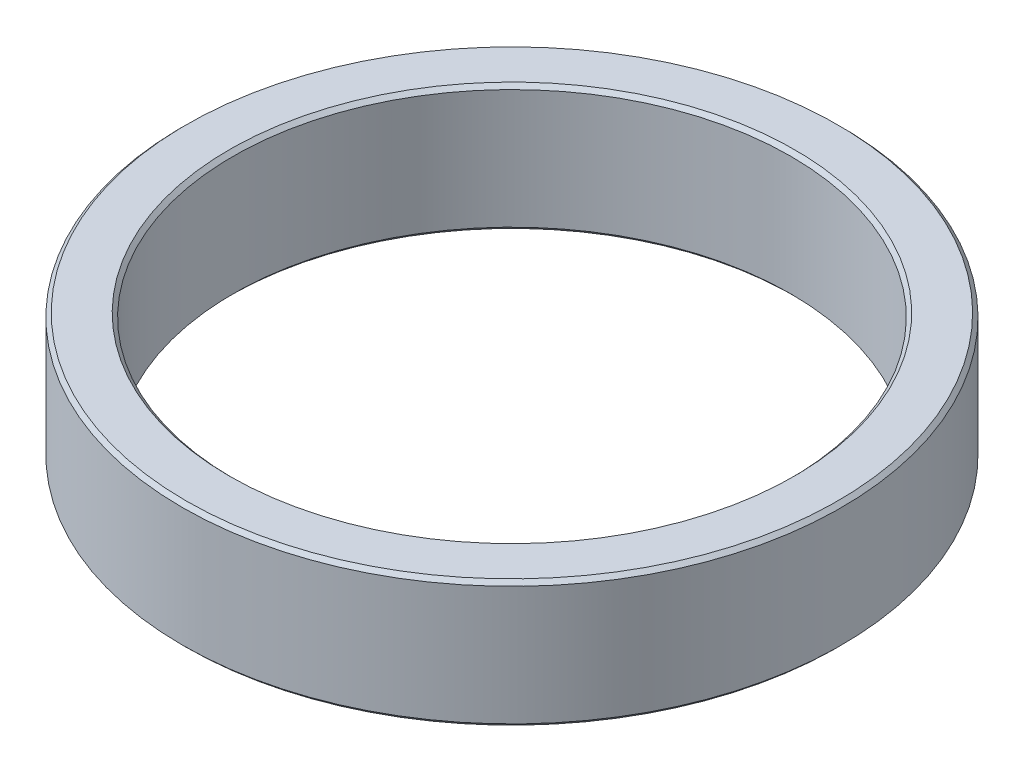
SolidWorks part; units mm, degrees
ref_plane "Front Plane" through (0, 0, 0) normal (0, 0, 1) x (1, 0, 0)
ref_plane "Top Plane" through (0, 0, 0) normal (0, 1, 0) x (1, 0, 0)
ref_plane "Right Plane" through (0, 0, 0) normal (1, 0, 0) x (0, 0, -1)
sketch "Sketch1" plane through (0, 0, 0) normal (0, 1, 0) x (1, 0, 0)
  circle A0 centre (0, 0) radius 13
  circle A1 centre (0, 0) radius 11
  dimension "D1" = 26
  dimension "D2" = 22
extrude "Boss-Extrude1" add sketch "Sketch1" along normal blind 5
chamfer "Chamfer1" distance 0.15 angle 45 4 edges at (0, 0, 11) (0, 0, 13) (0, 5, 11) (0, 5, 13)
